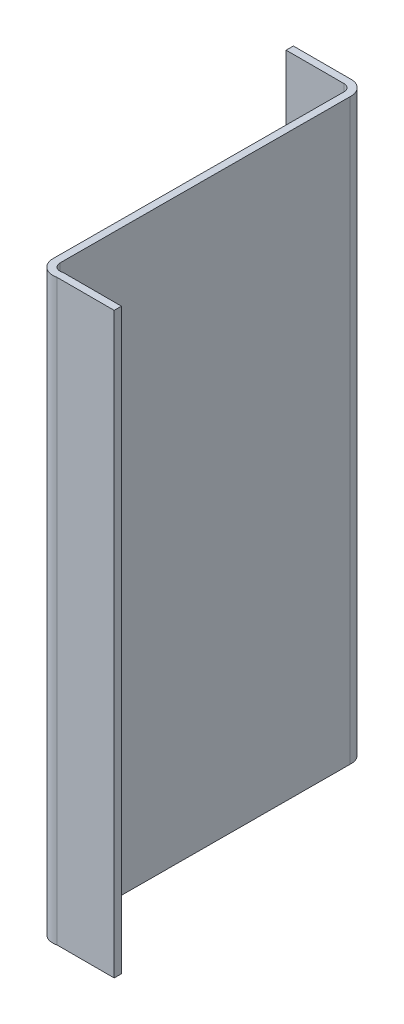
SolidWorks part; units mm, degrees
ref_plane "Front Plane" through (0, 0, 0) normal (0, 0, 1) x (1, 0, 0)
ref_plane "Top Plane" through (0, 0, 0) normal (0, 1, 0) x (1, 0, 0)
ref_plane "Right Plane" through (0, 0, 0) normal (1, 0, 0) x (0, 0, -1)
sketch "Sketch1" plane through (0, 0, 0) normal (0, 1, 0) x (1, 0, 0)
  line L0 (-46.7261, 153.6132) -> (-6.725, 153.6132)
  line L1 (0.7482, 145.477) -> (0, -54.523)
  line L2 (9.6607, -61.7333) -> (49.6619, -61.7333)
  arc A0 (-6.725, 153.6132) -> (0.7482, 145.477) centre (-6.725, 146.113) cw
  arc A1 (0, -54.523) -> (9.6607, -61.7333) centre (7.5002, -54.5511) ccw
  dimension "D1" = 200
  dimension "D3" = 7.5002
  dimension "D2" = 40.0011
extrude "Extrude-Thin1" add sketch "Sketch1" along normal blind 400 thin thin type mid plane wall 5
